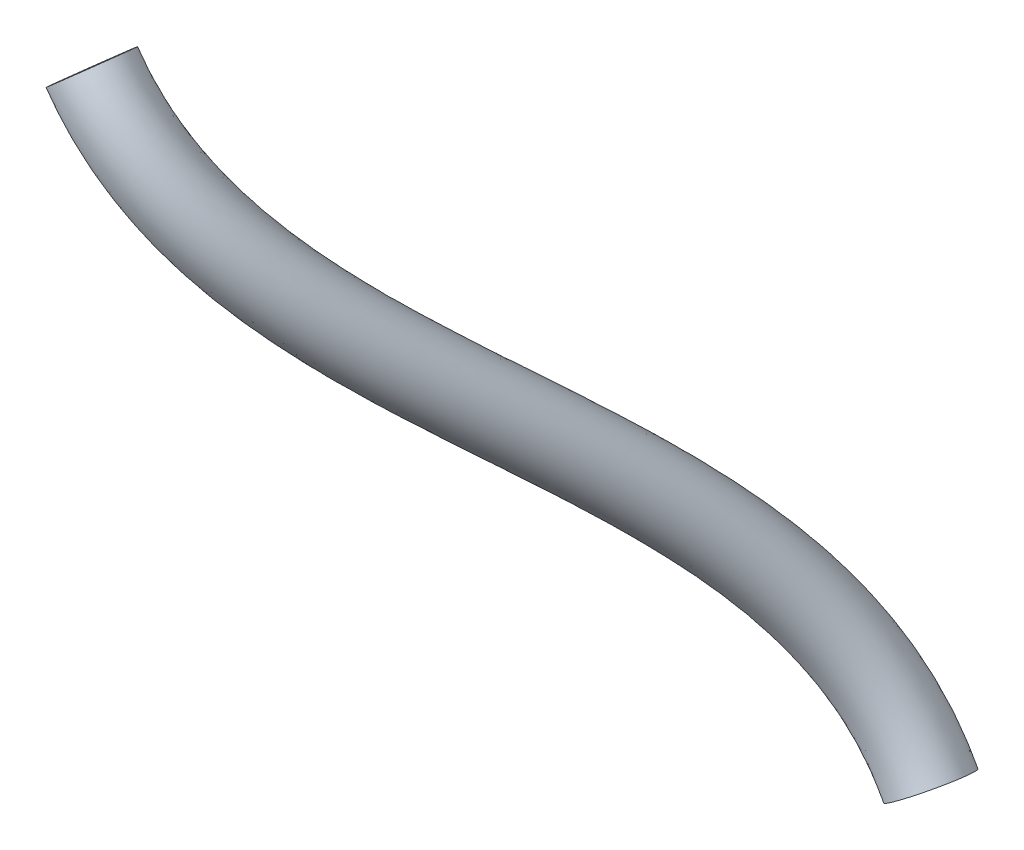
SolidWorks part; units mm, degrees
ref_plane "X-Y Datum" through (0, 0, 0) normal (0, 0, 1) x (1, 0, 0)
ref_plane "X-Z Datum" through (0, 0, 0) normal (0, 1, 0) x (1, 0, 0)
ref_plane "Y-Z Datum" through (0, 0, 0) normal (1, 0, 0) x (0, 0, -1)
sketch3d "3DSketch1"
  spline S0 degree 3 poles (-328.1555, -380.4052, 493.7693) (-350.588, -349.1634, 489.885) (-366.0654, -332.7868, 546.0657) (-391.2531, -304.0115, 542.9616) knots 0 0 0 0 1 1 1 1
  point P0 (-328.1555, -380.4052, 493.7693)
  point P1 (-332.6214, -374.2556, 493.7693)
  point P6 (-391.2531, -304.0115, 542.9616)
  point P10 (-387.2303, -308.597, 542.9616)
sweep "Sweep1" add path "3DSketch1" circular profile diameter 9.5 parameters "D3"=9.5
